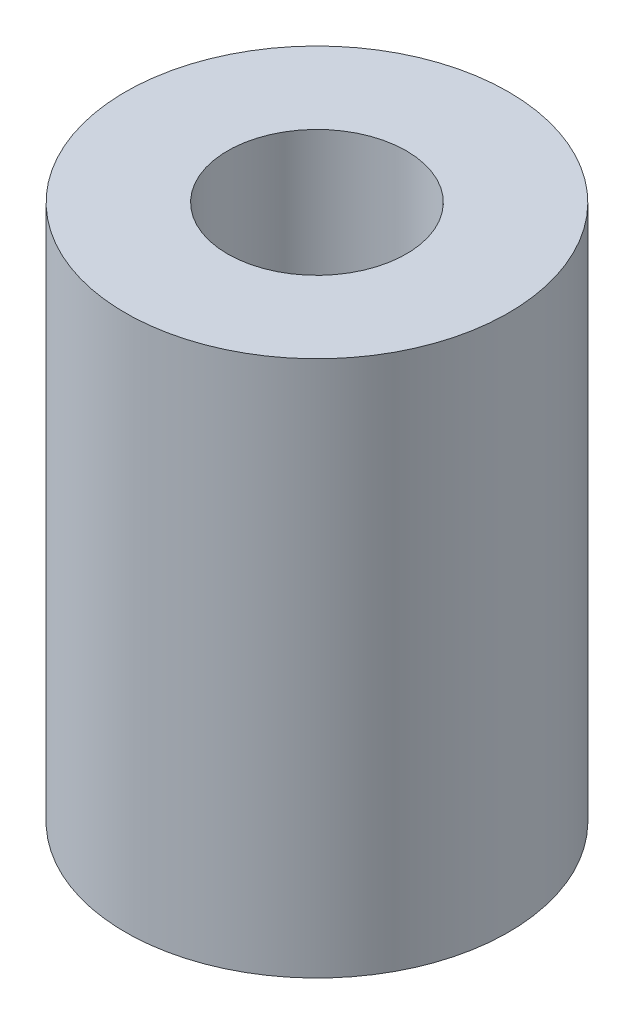
SolidWorks part; units mm, degrees
ref_plane "Front Plane" through (0, 0, 0) normal (0, 0, 1) x (1, 0, 0)
ref_plane "Top Plane" through (0, 0, 0) normal (0, 1, 0) x (1, 0, 0)
ref_plane "Right Plane" through (0, 0, 0) normal (1, 0, 0) x (0, 0, -1)
sketch "Sketch1" plane through (0, 0, 0) normal (0, 1, 0) x (1, 0, 0)
  circle A0 centre (0, 0) radius 3.75
  dimension "D1" = 7.5
extrude "Boss-Extrude1" add sketch "Sketch1" along normal blind 10.5
hole_wizard "Ø3.5 (3.5) Diameter Hole1" positions "Sketch2" profile "Sketch3" hole size "Ø3.5" standard "JIS" end condition through all
sketch "Sketch2" plane through (0, 10.5, 0) normal (0, 1, 0) x (1, 0, 0)
  point P0 (0, 0)
sketch "Sketch3" plane through (0, 10.5, 0) normal (1, 0, 0) x (0, 0, 1)
  line L0 (0, 0) -> (0, 10.5)
  line L1 (0, 10.5) -> (1.75, 10.5)
  line L2 (1.75, 10.5) -> (1.75, 0)
  line L5 (1.75, 0) -> (0, 0)
  line L11 (0, -6.35) -> (0, 107.95) construction
  dimension "Thru Hole Dia." = 3.5
  dimension "Thru Hole Depth" = 10.5
sketch "Sketch4" plane through (0, 0, 0) normal (0, -1, 0) x (1, 0, 0)
  circle A0 centre (0, 0) radius 4.75
  dimension "D1" = 9.5
